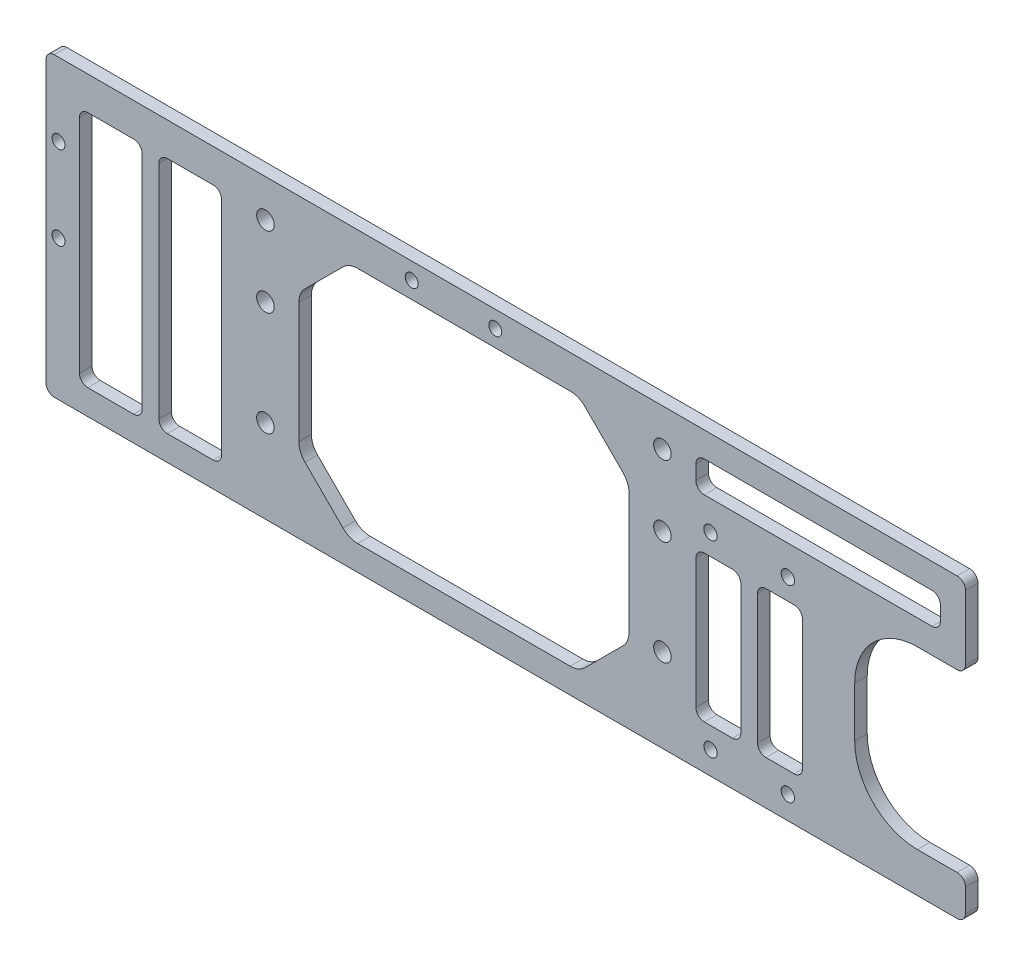
SolidWorks part; units mm, degrees
material "Thornel Mat VMA"
ref_plane "前视基准面" through (0, 0, 0) normal (0, 0, 1) x (1, 0, 0)
ref_plane "上视基准面" through (0, 0, 0) normal (0, 1, 0) x (1, 0, 0)
ref_plane "右视基准面" through (0, 0, 0) normal (1, 0, 0) x (0, 0, -1)
other "Configuration Table"
sketch "草图1" plane through (0, 0, 0) normal (0, 0, 1) x (1, 0, 0)
  line L0 (0, 0) -> (0, -50000) construction
  line L2 (0, 0) -> (50000, 0) construction
  line L3 (-100, 27) -> (100, 27)
  line L4 (-100, 27) -> (-100, -27)
  line L5 (-100, -27) -> (100, -27)
  line L6 (100, 27) -> (100, -27)
  line L7 (-100, 27) -> (100, -27) construction
  line L8 (-100, -27) -> (100, 27) construction
  line L9 (-47.5, 21) -> (-47.5, 4) construction
  line L10 (-47.5, 4) -> (-47.5, -21) construction
  circle A3 centre (-47.5, 21) radius 2.1
  circle A4 centre (-47.5, 4) radius 2.1
  circle A5 centre (-47.5, -21) radius 2.1
  circle A6 centre (47.5, -21) radius 2.1
  circle A7 centre (47.5, 4) radius 2.1
  circle A8 centre (47.5, 21) radius 2.1
  point P0 (0, 0)
  dimension "D1" = 47.5
  dimension "D3" = 6
  dimension "D4" = 17
  dimension "D6" = 4.2
  dimension "D2" = 200
  dimension "D5" = 25
extrude "凸台-拉伸1" add sketch "草图1" along normal blind 3
sketch "草图3" plane through (0, 0, 3) normal (0, 0, 1) x (1, 0, 0)
  line L1 (-100, -27) -> (100, -27)
  line L2 (-100, -27) -> (-100, -41)
  line L3 (-100, -41) -> (100, -41)
  line L4 (100, -27) -> (100, -41)
  dimension "D1" = 14
extrude "凸台-拉伸2" add sketch "草图3" against normal up to surface (3 mm away) up to face at (0, 0, 0)
sketch "草图2" plane through (0, 0, 3) normal (0, 0, 1) x (1, 0, 0)
  line L0 (-0.7542, -13) -> (49999.2458, -13) construction
  line L2 (59, -35.5) -> (77.5, -35.5) construction
  line L3 (59, -35.5) -> (59, 9.5) construction
  line L4 (59, 9.5) -> (77.5, 9.5) construction
  line L5 (77.5, -35.5) -> (77.5, 9.5) construction
  line L6 (59, -35.5) -> (77.5, 9.5) construction
  line L7 (59, 9.5) -> (77.5, -35.5) construction
  circle A0 centre (59, 9.5) radius 1.6
  circle A1 centre (77.5, 9.5) radius 1.6
  circle A2 centre (77.5, -35.5) radius 1.6
  circle A3 centre (59, -35.5) radius 1.6
  point P3 (68.25, -13)
  dimension "D3" = 68.25
  dimension "D4" = 3.2
  dimension "D1" = 45
  dimension "D2" = 18.5
  dimension "D5" = 13
extrude "切除-拉伸1" cut sketch "草图2" against normal blind 10
sketch "草图4" plane through (0, 0, 3) normal (0, 0, 1) x (1, 0, 0)
  line L1 (-100, 27) -> (120, 27)
  line L2 (-100, 27) -> (-100, 30)
  line L3 (-100, 30) -> (120, 30)
  line L4 (120, 27) -> (120, 30)
  line L5 (100, -41) -> (120, -41)
  line L6 (100, -41) -> (100, 27)
  line L7 (100, 27) -> (120, 27)
  line L8 (120, -41) -> (120, 27)
  line M9 (100, -41) -> (100, 27)
  dimension "D1" = 3
  dimension "D2" = 20
extrude "凸台-拉伸3" add sketch "草图4" against normal up to surface (3 mm away) contours L5 L8 L1 M9 up to face at (60.6, -35.5, 0)
sketch "草图5" plane through (0, 0, 3) normal (0, 0, 1) x (1, 0, 0)
  line L0 (120, -41) -> (120, 30) construction
  line L1 (120, 10.55) -> (93.5, 10.55)
  line L2 (120, 10.55) -> (120, -31.45)
  line L3 (120, -31.45) -> (93.5, -31.45)
  line L4 (93.5, 10.55) -> (93.5, -31.45)
  line L5 (-100, 30) -> (120, 30) construction
  dimension "D1" = 19.45
  dimension "D2" = 42
  dimension "D3" = 26.5
extrude "切除-拉伸2" cut sketch "草图5" against normal blind 10
fillet "圆角1" radius 15 2 edges at (93.5, -31.45, 1.5) (93.5, 10.55, 1.5)
fillet "圆角2" radius 2 6 edges at (120, 30, 1.5) (-100, 30, 1.5) (-100, -41, 1.5) (120, -41, 1.5) (120, -31.45, 1.5) (120, 10.55, 1.5)
sketch "草图14" plane through (0, 0, 0) normal (0, 0, -1) x (-1, 0, 0)
  line L0 (-118, 30) -> (98, 30) construction
  line L1 (-39.5, -35) -> (39.5, -35)
  line L2 (-39.5, -35) -> (-39.5, 22)
  line L3 (-39.5, 22) -> (39.5, 22)
  line L4 (39.5, -35) -> (39.5, 22)
  line L5 (-39.5, -35) -> (39.5, 22) construction
  line L6 (-39.5, 22) -> (39.5, -35) construction
  line L7 (-118, -41) -> (98, -41) construction
  circle A0 centre (-47.5, 4) radius 2.1 construction
  circle A1 centre (47.5, 21) radius 2.1 construction
  point P0 (0, -6.5)
  point P5 (36.6054, 15.8817)
  point P6 (2.1943, -6.8364)
  dimension "D1" = 8
  dimension "D2" = 8
  dimension "D3" = 8
  dimension "D4" = 6
extrude "切除-拉伸7" cut sketch "草图14" against normal blind 10
chamfer "倒角1" distance 12 angle 45 4 edges at (-39.5, 22, 1.5) (-39.5, -35, 1.5) (39.5, -35, 1.5) (39.5, 22, 1.5)
fillet "圆角4" radius 5 8 edges at (-27.5, -35, 1.5) (27.5, -35, 1.5) (39.5, -23, 1.5) (39.5, 10, 1.5) (27.5, 22, 1.5) (-27.5, 22, 1.5) (-39.5, 10, 1.5) (-39.5, -23, 1.5)
sketch "草图15" plane through (0, 0, 0) normal (0, 0, -1) x (-1, 0, 0)
  line L0 (77, 22) -> (77, -35)
  line L1 (55.5, -35) -> (92, -35)
  line L2 (55.5, -35) -> (55.5, 22)
  line L3 (55.5, 22) -> (92, 22)
  line L4 (92, -35) -> (92, 22)
  line L5 (55.5, -35) -> (92, 22) construction
  line L6 (55.5, 22) -> (92, -35) construction
  line L7 (-25.4289, -35) -> (25.4289, -35) construction
  line L8 (47.5, 4) -> (39.5, 4) construction
  line L9 (39.5, -20.9289) -> (39.5, 7.9289) construction
  line L10 (47.5, 4) -> (55.5, 4) construction
  line L11 (25.4289, 22) -> (-25.4289, 22) construction
  line L12 (92, 22) -> (100, 22) construction
  line L13 (100, 28) -> (100, -39) construction
  line L14 (-47.5, 4) -> (-55.5, 4) construction
  line L15 (-77.5, -35.5) -> (-59, -35.5) construction
  line L16 (-77.5, -35.5) -> (-77.5, 9.5) construction
  line L17 (-77.5, 9.5) -> (-59, 9.5) construction
  line L18 (-59, -35.5) -> (-59, 9.5) construction
  line L19 (-77.5, -35.5) -> (-59, 9.5) construction
  line L20 (-77.5, 9.5) -> (-59, -35.5) construction
  line L21 (-81, -30.5) -> (-55.5, -30.5)
  line L22 (-81, -30.5) -> (-81, 4.5)
  line L23 (-81, 4.5) -> (-55.5, 4.5)
  line L24 (-55.5, -30.5) -> (-55.5, 4.5)
  line L25 (-81, -30.5) -> (-55.5, 4.5) construction
  line L26 (-81, 4.5) -> (-55.5, -30.5) construction
  line L27 (73, 22) -> (73, -35)
  line L28 (58, 22) -> (58, -35)
  line L29 (-70.25, 4.5) -> (-70.25, -30.5)
  line L30 (-66.25, 4.5) -> (-66.25, -30.5)
  line L31 (-68.25, 4.5) -> (-68.25, 50004.5) construction
  circle A0 centre (-59, 9.5) radius 1.6 construction
  point P0 (73.75, -6.5)
  point P18 (-68.25, -13)
  point P27 (-68.25, -13)
  point P47 (-68.25, 4.5)
  dimension "D1" = 5
  dimension "D2" = 15
  dimension "D3" = 4
  dimension "D4" = 15
  dimension "D5" = 4
extrude "切除-拉伸10" cut sketch "草图15" against normal blind 10 contours L3 L28 L1 L27 | L1 L4 L3 L0 | L23 L30 L21 L24 | L29 L23 L22 L21
fillet "圆角5" radius 2 16 edges at (81, -30.5, 1.5) (81, 4.5, 1.5) (70.25, 4.5, 1.5) (70.25, -30.5, 1.5) (55.5, -30.5, 1.5) (66.25, -30.5, 1.5) (66.25, 4.5, 1.5) (55.5, 4.5, 1.5) (-73, -35, 1.5) (-58, -35, 1.5) (-58, 22, 1.5) (-73, 22, 1.5) (-77, -35, 1.5) (-77, 22, 1.5) (-92, 22, 1.5) (-92, -35, 1.5)
sketch "草图16" plane through (0, 0, 0) normal (0, 0, -1) x (-1, 0, 0)
  line L0 (-87.7459, 20.275) -> (-55.5, 21) construction
  line L1 (-114, 16.55) -> (-61.4919, 16.55)
  line L2 (-114, 16.55) -> (-114, 24)
  line L3 (-114, 24) -> (-61.4919, 24)
  line L4 (-61.4919, 16.55) -> (-61.4919, 24)
  line L5 (-114, 16.55) -> (-61.4919, 24) construction
  line L6 (-114, 24) -> (-61.4919, 16.55) construction
  line L9 (-47.5, 21) -> (-55.5, 21) construction
  line L10 (-87.7459, 20.275) -> (-120, 20.275) construction
  line L11 (-120, 28) -> (-120, 12.55) construction
  line L12 (-114, 24) -> (-114, 30) construction
  line L13 (-118, 30) -> (98, 30) construction
  line L14 (-114, 16.55) -> (-114, 10.55) construction
  line L15 (-118, 10.55) -> (-108.5, 10.55) construction
  line L16 (-114, 24) -> (-120, 24) construction
  line L18 (-61.4919, 24) -> (-55.5, 24)
  line L19 (-61.4919, 24) -> (-61.4919, 16.55)
  line L20 (-61.4919, 16.55) -> (-55.5, 16.55)
  line L21 (-55.5, 24) -> (-55.5, 16.55)
  point P0 (-87.7459, 20.275)
  point P4 (0, 0)
  point P24 (0, 0)
  dimension "D1" = 8
  dimension "D2" = 6
extrude "切除-拉伸11" cut sketch "草图16" against normal blind 10 contours L1 L4 L3 L2 | L21 L18 L4 L20
fillet "圆角6" radius 2 4 edges at (114, 16.55, 1.5) (114, 24, 1.5) (55.5, 24, 1.5) (55.5, 16.55, 1.5)
sketch "草图17" plane through (0, 0, 0) normal (0, 0, -1) x (-1, 0, 0)
  line L0 (-7.5, 26) -> (12.5, 26) construction
  line L1 (-118, 30) -> (98, 30) construction
  line L3 (100, 28) -> (100, -39) construction
  circle A0 centre (-7.5, 26) radius 1.55
  circle A1 centre (12.5, 26) radius 1.55
  dimension "D1" = 20
  dimension "D3" = 3.1
  dimension "D4" = 87.5
  dimension "D2" = 4
extrude "切除-拉伸12" cut sketch "草图17" against normal blind 10
sketch "草图18" plane through (0, 0, 0) normal (0, 0, -1) x (-1, 0, 0)
  line L0 (97, 12.5) -> (97, -7.5) construction
  line L1 (-118, 30) -> (98, 30) construction
  line L2 (100, 28) -> (100, -39) construction
  circle A0 centre (97, 12.5) radius 1.55
  circle A1 centre (97, -7.5) radius 1.55
  dimension "D1" = 17.5
  dimension "D4" = 3.1
  dimension "D2" = 20
  dimension "D3" = 3
extrude "切除-拉伸13" cut sketch "草图18" against normal blind 10
